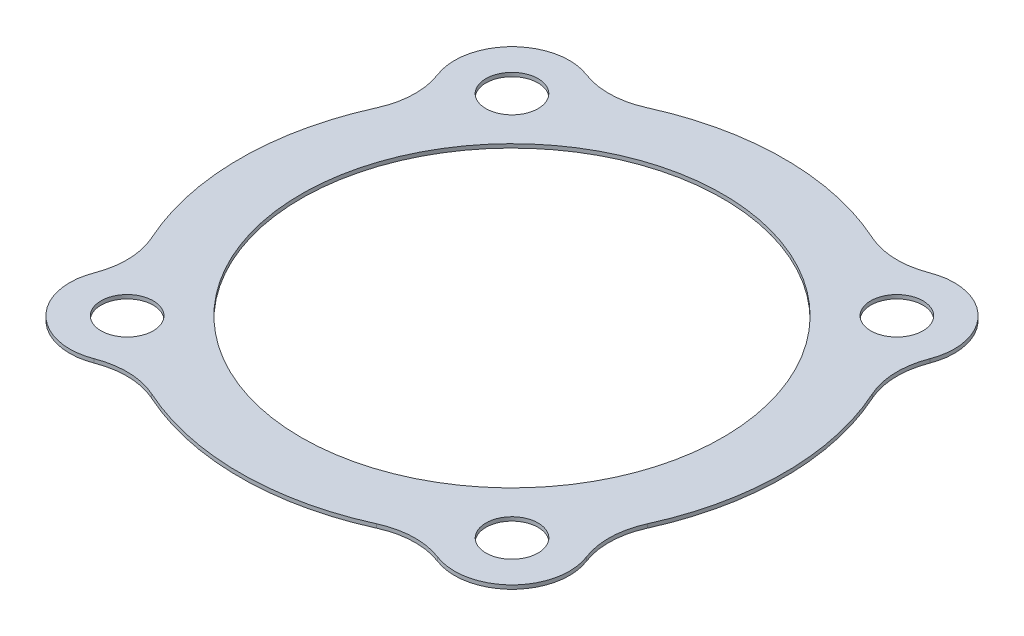
SolidWorks part; units mm, degrees
material "VITON"
ref_plane "Front Plane" through (0, 0, 0) normal (0, 0, 1) x (1, 0, 0)
ref_plane "Top Plane" through (0, 0, 0) normal (0, 1, 0) x (1, 0, 0)
ref_plane "Right Plane" through (0, 0, 0) normal (1, 0, 0) x (0, 0, -1)
sketch "Sketch1" plane through (0, 0, 0) normal (0, 1, 0) x (1, 0, 0)
  circle A0 centre (0, 0) radius 45.085
extrude "Base Extrude" add sketch "Sketch1" along normal blind 0.635
sketch "Sketch2" plane through (0, 0.635, 0) normal (0, 1, 0) x (1, 0, 0)
  circle A0 centre (0, 0) radius 34.925
extrude "Base Cut" cut sketch "Sketch2" against normal through all
sketch "Sketch3" plane through (0, 0.635, 0) normal (0, 1, 0) x (1, 0, 0)
  line L0 (-45.085, 0) -> (45.085, 0) construction
  line L1 (0, 45.085) -> (0, -45.085) construction
  line L2 (0, 0) -> (-31.8799, 31.8799) construction
  line L3 (-31.8799, 31.8799) -> (31.8799, -31.8799) construction
  line L4 (0, 0) -> (-31.8799, -31.8799) construction
  line L5 (-31.8799, -31.8799) -> (31.8799, 31.8799) construction
  circle A0 centre (0, 0) radius 45.085 construction
  circle A1 centre (-31.8799, 31.8799) radius 9.525
extrude "Corner Extrude" add sketch "Sketch3" against normal blind 0.635
sketch "Sketch4" plane through (0, 0.635, 0) normal (0, 1, 0) x (1, 0, 0)
  circle A0 centre (-31.8799, 31.8799) radius 4.318
  point P0 (-31.8799, 31.8799)
extrude "Corner Cut" cut sketch "Sketch4" against normal through all
fillet "Fillet" radius 12.7 2 edges at (-24.4709, 0.3175, -37.866) (-37.866, 0.3175, -24.4709)
pattern_circular "CirPattern" count 4 over 360 about axis through (0, 0, 0) along (0, 1, 0) of "Fillet", "Corner Cut", "Corner Extrude"
